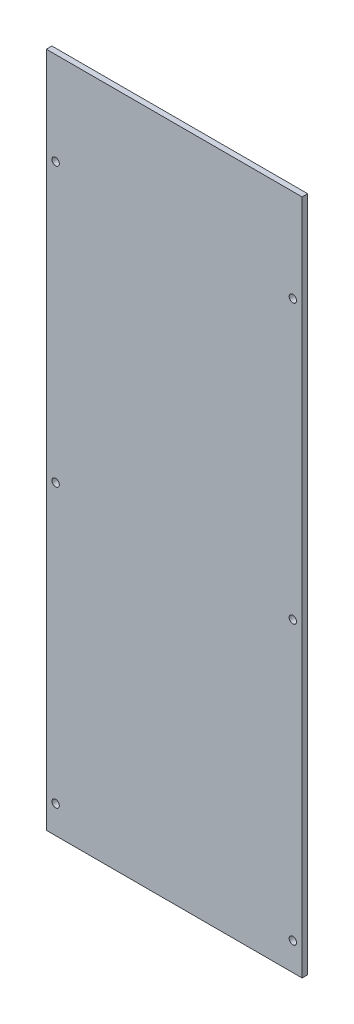
SolidWorks part; units mm, degrees
material "Acrylic (Medium-high impact)"
ref_plane "Front Plane" through (0, 0, 0) normal (0, 0, 1) x (1, 0, 0)
ref_plane "Top Plane" through (0, 0, 0) normal (0, 1, 0) x (1, 0, 0)
ref_plane "Right Plane" through (0, 0, 0) normal (1, 0, 0) x (0, 0, -1)
sketch "Sketch1" plane through (0, 0, 0) normal (0, 0, 1) x (1, 0, 0)
  line L0 (5, -50) -> (5, 0) construction
  line L5 (133, -50) -> (133, 0) construction
  line L6 (0, 0) -> (138, 0)
  line L8 (0, 0) -> (0, -365)
  line L9 (138, 0) -> (138, -365)
  line L10 (0, -365) -> (138, -365)
  circle A0 centre (133, -350) radius 2
  circle A1 centre (5, -350) radius 2
  circle A2 centre (133, -200) radius 2
  circle A3 centre (5, -200) radius 2
  circle A4 centre (133, -50) radius 2
  circle A5 centre (5, -50) radius 2
  dimension "D3" = 4
  dimension "D1" = 5
  dimension "D2" = 5
  dimension "D4" = 133
  dimension "D5" = 50
  dimension "D6" = 200
  dimension "D7" = 350
  dimension "D8" = 365
extrude "Boss-Extrude1" add sketch "Sketch1" along normal blind 3
